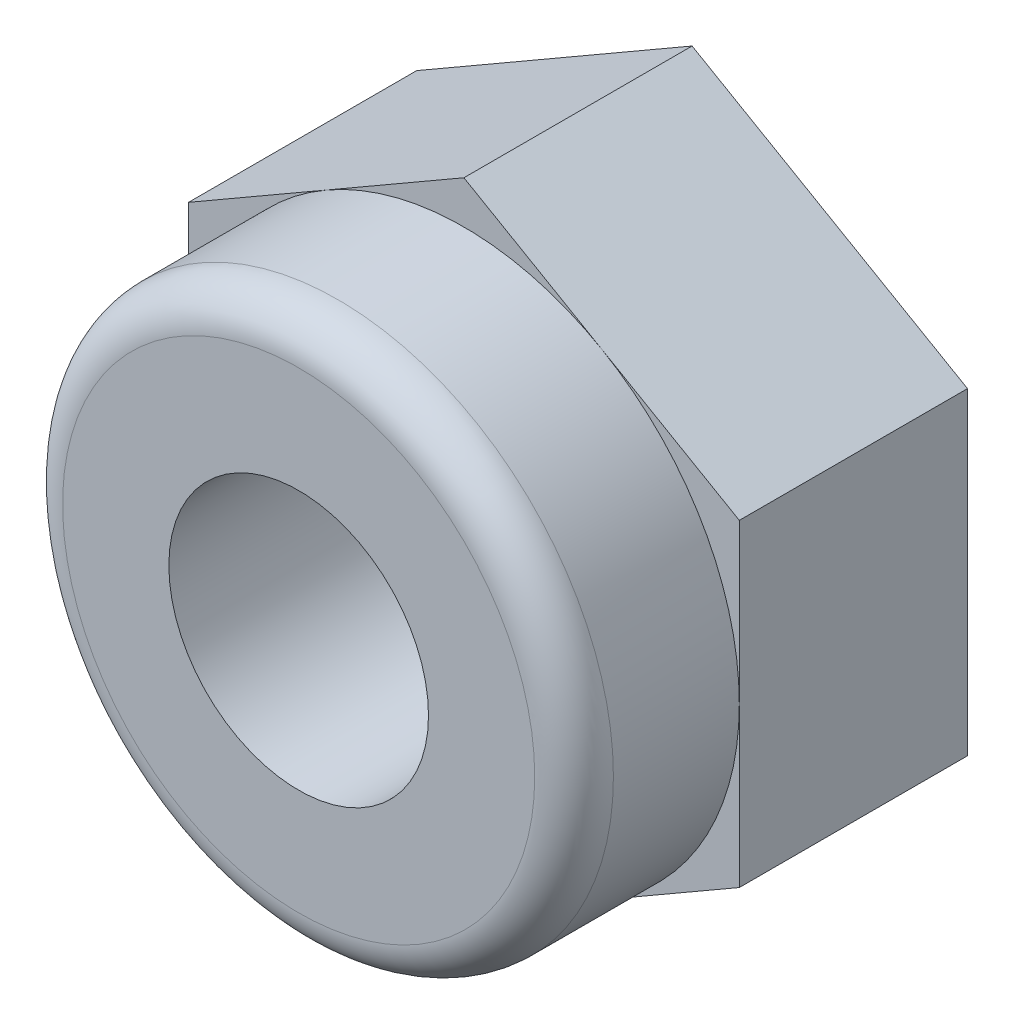
SolidWorks part; units mm, degrees
material "AISI 304"
ref_plane "前视基准面" through (0, 0, 0) normal (0, 0, 1) x (1, 0, 0)
ref_plane "上视基准面" through (0, 0, 0) normal (0, 1, 0) x (1, 0, 0)
ref_plane "右视基准面" through (0, 0, 0) normal (1, 0, 0) x (0, 0, -1)
sketch "草图1" plane through (0, 0, 0) normal (0, 0, 1) x (1, 0, 0)
  line L1 (0, 4.0415) -> (-3.5, 2.0207)
  line L2 (-3.5, 2.0207) -> (-3.5, -2.0207)
  line L3 (-3.5, -2.0207) -> (0, -4.0415)
  line L4 (0, -4.0415) -> (3.5, -2.0207)
  line L5 (3.5, -2.0207) -> (3.5, 2.0207)
  line L6 (3.5, 2.0207) -> (0, 4.0415)
  circle A0 centre (0, 0) radius 3.5 construction
  dimension "D1" = 7
extrude "凸台-拉伸1" add sketch "草图1" along normal blind 2.9
sketch "草图2" plane through (0, 0, 2.9) normal (0, 0, 1) x (1, 0, 0)
  circle A0 centre (0, 0) radius 3.5
extrude "凸台-拉伸2" add sketch "草图2" along normal blind 2.1
fillet "圆角1" radius 0.5 1 edges at (3.5, 0, 5)
hole_wizard "M4 螺纹孔1" positions "草图3" profile "草图4" tap size "M4" standard "GB" end condition through all
sketch "草图3" plane through (0, 0, 5) normal (0, 0, 1) x (1, 0, 0)
  point P0 (0, 0)
sketch "草图4" plane through (0, 0, 5) normal (1, 0, 0) x (0, -1, 0)
  line L0 (0, 0) -> (0, 5)
  line L1 (0, 5) -> (1.65, 5)
  line L2 (1.65, 5) -> (1.65, 0)
  line L5 (1.65, 0) -> (0, 0)
  line L11 (0, -6.35) -> (0, 107.95) construction
  dimension "通孔螺纹孔钻头直径" = 3.3
  dimension "通孔螺纹孔钻头深度" = 5
cosmetic thread "孔螺蚊线1" parameters "D2"=4
